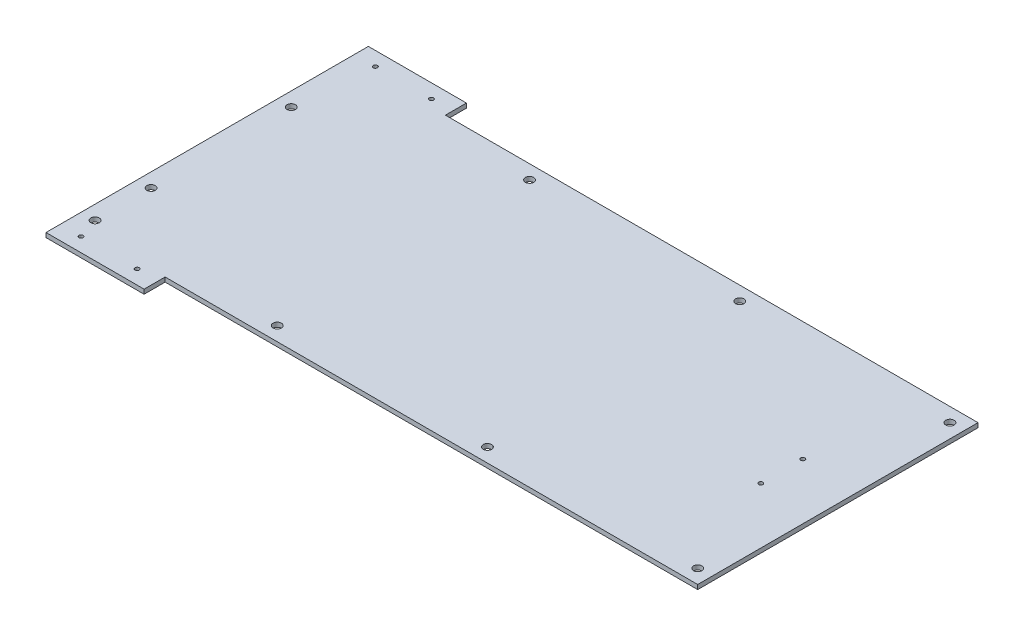
SolidWorks part; units mm, degrees
ref_plane "Front Plane" through (0, 0, 0) normal (0, 0, 1) x (1, 0, 0)
ref_plane "Top Plane" through (0, 0, 0) normal (0, 1, 0) x (1, 0, 0)
ref_plane "Right Plane" through (0, 0, 0) normal (1, 0, 0) x (0, 0, -1)
sketch "Sketch1" plane through (0, 0, 0) normal (0, 1, 0) x (1, 0, 0)
  line L1 (70, 110.4681) -> (450, 110.4681)
  line L3 (70, 310.4681) -> (450, 310.4681)
  line L4 (450, 110.4681) -> (450, 310.4681)
  line L5 (0, 325.4681) -> (70, 325.4681)
  line L6 (70, 325.4681) -> (70, 310.4681)
  line L8 (0, 95.4681) -> (70, 95.4681)
  line L9 (70, 95.4681) -> (70, 110.4681)
  line L10 (35, 325.4681) -> (35, 95.4681) construction
  line L12 (0, 95.4681) -> (0, 325.4681)
  line L13 (0, 210.4681) -> (449.8782, 210.4681) construction
  line L14 (290, 300.4681) -> (290, 120.4681) construction
  line L15 (140, 300.4681) -> (140, 120.4681) construction
  circle A0 centre (55, 315.4681) radius 1.5
  circle A1 centre (15, 315.4681) radius 1.5
  circle A2 centre (55, 105.4681) radius 1.5
  circle A3 centre (15, 105.4681) radius 1.5
  circle A4 centre (410, 225.4681) radius 1.5
  circle A5 centre (410, 195.4681) radius 1.5
  circle A7 centre (10, 260.4681) radius 3
  circle A9 centre (440, 300.4681) radius 3
  circle A10 centre (140, 300.4681) radius 3
  circle A12 centre (290, 300.4681) radius 3
  circle A15 centre (440, 120.4681) radius 3
  circle A16 centre (290, 120.4681) radius 3
  circle A18 centre (140, 120.4681) radius 3
  circle A19 centre (10, 120.4681) radius 3
  circle A20 centre (10, 160.4681) radius 3
  point P12 (15, 105.4681)
  point P17 (55, 105.4681)
  dimension "D6" = 20
  dimension "D8" = 15
  dimension "D10" = 3
  dimension "D16" = 10
  dimension "D17" = 10
  dimension "D20" = 150
  dimension "D26" = 6
  dimension "D28" = 6
  dimension "D30" = 6
  dimension "D31" = 6
  dimension "D1" = 15
  dimension "D2" = 70
  dimension "D3" = 70
  dimension "D4" = 15
  dimension "D5" = 200
  dimension "D7" = 20
  dimension "D9" = 15
  dimension "D11" = 40
  dimension "D12" = 40
  dimension "D13" = 450
  dimension "D14" = 5
  dimension "D15" = 5
  dimension "D18" = 10
  dimension "D19" = 50
extrude "Boss-Extrude1" add sketch "Sketch1" along normal blind 3.175
